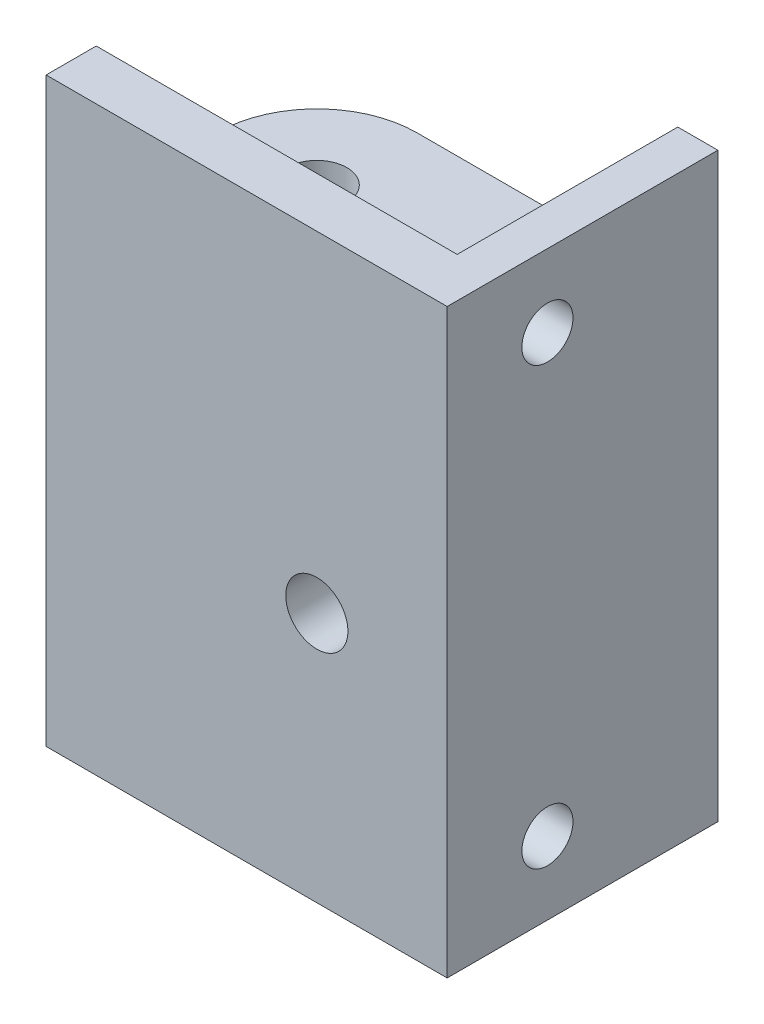
SolidWorks part; units mm, degrees
ref_plane "前视基准面" through (0, 0, 0) normal (0, 0, 1) x (1, 0, 0)
ref_plane "上视基准面" through (0, 0, 0) normal (0, 1, 0) x (1, 0, 0)
ref_plane "右视基准面" through (0, 0, 0) normal (1, 0, 0) x (0, 0, -1)
other "Configuration Table"
sketch "草图1" plane through (0, 0, 0) normal (0, 1, 0) x (1, 0, 0)
  line L0 (-20, 13.5) -> (5, 13.5)
  line L1 (20, -1.5) -> (20, -13.5)
  line L6 (-20, -13.5) -> (20, -13.5)
  line L7 (-20, -13.5) -> (-20, 13.5)
  arc A0 (20, -1.5) -> (5, 13.5) centre (5, -1.5) ccw
extrude "凸台-拉伸1" add sketch "草图1" along normal blind 58 contours L1 L6 L7 L0 A0
sketch "草图2" plane through (0, 0, 13.5) normal (0, 0, 1) x (1, 0, 0)
  circle A0 centre (-7, 33) radius 3
extrude "切除-拉伸1" cut sketch "草图2" against normal blind 58 contours A0
sketch "草图3" plane through (0, 0, -13.5) normal (0, 0, -1) x (-1, 0, 0)
  line L0 (20, 58) -> (20, 0)
  line L1 (20, 29) -> (-5, 29)
  line L2 (-5, 58) -> (-5, 0) construction
  line L3 (-5, 29) -> (-5, 43.5)
  line L4 (-5, 29) -> (-5, 14.5)
  line L5 (-5, 43.5) -> (20, 43.5)
  line L6 (-5, 14.5) -> (20, 14.5)
  line L7 (20, 43.5) -> (-20, 43.5)
  line L8 (20, 43.5) -> (20, 58)
  line L9 (20, 58) -> (-20, 58)
  line L10 (-20, 43.5) -> (-20, 58)
  line L12 (20, 14.5) -> (-20, 14.5)
  line L13 (20, 14.5) -> (20, 0)
  line L14 (20, 0) -> (-20, 0)
  line L15 (-20, 14.5) -> (-20, 0)
  line M8 (-5, 0) -> (20, 0)
  line M9 (20, 0) -> (20, 58)
  line M10 (20, 58) -> (-5, 58)
  line M11 (-5, 58) -> (-5, 0)
extrude "切除-拉伸2" cut sketch "草图3" against normal blind 22 contours L10 L7 L9 M11 | L12 L15 L14 M11 | L6 M11 M8 M9 | L5 M11 M9 M10
sketch "草图5" plane through (0, 0, 8.5) normal (0, 0, -1) x (-1, 0, 0)
  line L0 (20, 43.5) -> (-5, 43.5) construction
  line L1 (20, 58) -> (16, 58)
  line L2 (20, 58) -> (20, 43.5)
  line L3 (20, 43.5) -> (16, 43.5)
  line L4 (16, 58) -> (16, 43.5)
  line L5 (20, 14.5) -> (-5, 14.5) construction
  line L6 (20, 0) -> (16, 0)
  line L7 (20, 0) -> (20, 14.5)
  line L8 (20, 14.5) -> (16, 14.5)
  line L9 (16, 0) -> (16, 14.5)
extrude "凸台-拉伸2" add sketch "草图5" along normal blind 22 contours L9 L6 L7 L8 | L2 L1 L4 L3
sketch "草图8" plane through (-20, 0, 0) normal (-1, 0, 0) x (0, 0, 1)
  line L0 (13.5, 58) -> (3.5, 58)
  line L2 (-13.5, 58) -> (8.5, 58) construction
  line L3 (3.5, 58) -> (3.5, 43.5)
  line L4 (8.5, 43.5) -> (1.5, 43.5) construction
  line L5 (13.5, 0) -> (3.5, 0)
  line L6 (-13.5, 0) -> (8.5, 0) construction
  line L7 (3.5, 0) -> (3.5, 14.5)
  line L8 (8.5, 14.5) -> (1.5, 14.5) construction
  circle A0 centre (3.5, 50.75) radius 2.55
  circle A1 centre (3.5, 7.25) radius 2.55
extrude "切除-拉伸3" cut sketch "草图8" against normal blind 22 contours L3 A0 | L3 A0 | L7 A1 | L7 A1
sketch "草图10" plane through (0, 43.5, 0) normal (0, 1, 0) x (1, 0, 0)
  line L0 (20, -13.5) -> (20, -6.5)
  line L1 (20, -8.5) -> (20, -1.5) construction
  line L6 (20, 13.5) -> (20, -6.5)
  line L8 (-16, 13.5) -> (5, 13.5) construction
  line L9 (0, 13.5) -> (20, 13.5)
  arc A0 (20, -6.5) -> (0, 13.5) centre (20, 13.5) cw
  line M9 (5, 13.5) -> (-16, 13.5)
  line M12 (20, -8.5) -> (20, -1.5)
  arc M13 (20, -1.5) -> (5, 13.5) centre (5, -1.5) ccw
extrude "切除-拉伸4" cut sketch "草图10" against normal blind 30 contours A0 M12 M13 M9 | L9 L6 M13
sketch "草图11" plane through (0, 43.5, 0) normal (0, 1, 0) x (1, 0, 0)
  line L0 (0, 13.5) -> (5, 13.5)
  line L2 (20, -1.5) -> (20, -6.5)
  arc A0 (5, 13.5) -> (20, -1.5) centre (5, -1.5) cw
  arc A1 (0, 13.5) -> (20, -6.5) centre (20, 13.5) ccw
  arc A2 (0, 13.5) -> (20, -6.5) centre (20, 13.5) ccw construction
  circle A3 centre (9.5, 4) radius 1.51
  arc M15 (20, -6.5) -> (0, 13.5) centre (20, 13.5) cw
extrude "凸台-拉伸5" add sketch "草图11" against normal blind 4 contours A0 L0 L2 A3 M15
sketch "草图13" plane through (0, 14.5, 0) normal (0, -1, 0) x (1, 0, 0)
  line L0 (0, -13.5) -> (5, -13.5)
  line L2 (20, 6.5) -> (20, 1.5)
  arc A0 (0, -13.5) -> (20, 6.5) centre (20, -13.5) cw
  arc A1 (20, 1.5) -> (5, -13.5) centre (5, 1.5) cw
extrude "凸台-拉伸6" add sketch "草图13" against normal blind 4 contours A1 L2 A0 L0
sketch "草图17" plane through (0, 43.5, 0) normal (0, 1, 0) x (1, 0, 0)
  line L0 (20, -1.5) -> (20, 13.5)
  line L1 (20, -1.5) -> (20, -6.5)
  line L2 (20, -8.5) -> (20, -1.5) construction
  line L3 (-16, 13.5) -> (5, 13.5) construction
  line L4 (0, 13.5) -> (20, 13.5)
  line L6 (5.8579, -0.6421) -> (12.9289, 6.4289)
  arc A0 (20, -6.5) -> (0, 13.5) centre (20, 13.5) cw
  circle A1 centre (12.9289, 6.4289) radius 1.51
sketch "草图18" plane through (0, 0, 13.5) normal (0, 0, 1) x (1, 0, 0)
  circle A0 centre (-7, 33) radius 3.05
extrude "切除-拉伸7" cut sketch "草图18" against normal blind 50
extrude "切除-拉伸8" cut sketch "草图17" against normal blind 50
sketch "草图19" plane through (0, 43.5, 0) normal (0, 1, 0) x (1, 0, 0)
  line L2 (10, 13.5) -> (5, 13.5)
  line L3 (20, 3.5) -> (20, -1.5)
  arc A0 (5, 13.5) -> (20, -1.5) centre (5, -1.5) cw
  arc A1 (10, 13.5) -> (20, 3.5) centre (10, 3.5) cw
extrude "凸台-拉伸7" add sketch "草图19" against normal blind 4 contours L3 A0 L2 A1
sketch "草图20" plane through (0, 43.5, 0) normal (0, 1, 0) x (1, 0, 0)
  line L2 (20, 3.5) -> (20, -8.5)
  line L3 (20, -8.5) -> (-16, -8.5)
  line L4 (-16, -8.5) -> (-16, 13.5)
  line L5 (-16, 13.5) -> (10, 13.5)
  arc A0 (10, 13.5) -> (20, 3.5) centre (10, 3.5) cw
  arc A1 (20, 3.5) -> (10, 13.5) centre (10, 3.5) ccw construction
  circle A2 centre (12.9289, 6.4289) radius 1.51
extrude "凸台-拉伸8" add sketch "草图20" along normal blind 1 contours A0 L2 L3 L4 L5
sketch "草图21" plane through (0, 44.5, 0) normal (0, 1, 0) x (1, 0, 0)
  circle A0 centre (12.9289, 6.4289) radius 3
  circle M2 centre (12.9289, 6.4289) radius 1.51
extrude "切除-拉伸9" cut sketch "草图21" against normal blind 2 contours A0 M2
sketch "草图22" plane through (0, 14.5, 0) normal (0, -1, 0) x (-1, 0, 0)
  line L0 (-5, 13.5) -> (-10, 13.5)
  line L1 (-20, -1.5) -> (-20, 3.5)
  arc A0 (-10, 13.5) -> (-20, 3.5) centre (-10, 3.5) ccw
  arc A1 (-5, 13.5) -> (-20, -1.5) centre (-5, -1.5) ccw
  arc A2 (-5, 13.5) -> (-20, -1.5) centre (-5, -1.5) ccw construction
extrude "凸台-拉伸9" add sketch "草图22" against normal blind 4 contours L0 A0 L1 A1
sketch "草图23" plane through (0, 14.5, 0) normal (0, -1, 0) x (-1, 0, 0)
  line L0 (16, -8.5) -> (16, 13.5)
  line L1 (16, 13.5) -> (-10, 13.5)
  line L4 (-20, 3.5) -> (-20, -8.5)
  line L5 (-20, -8.5) -> (16, -8.5)
  arc A0 (-10, 13.5) -> (-20, 3.5) centre (-10, 3.5) ccw
  arc A1 (-10, 13.5) -> (-20, 3.5) centre (-10, 3.5) ccw construction
  circle A2 centre (-12.9289, 6.4289) radius 1.51
extrude "凸台-拉伸10" add sketch "草图23" along normal blind 1 contours A0 L4 L5 L0 L1
sketch "草图24" plane through (0, 13.5, 0) normal (0, -1, 0) x (-1, 0, 0)
  circle A0 centre (-12.9289, 6.4289) radius 3
extrude "切除-拉伸10" cut sketch "草图24" against normal blind 2
sketch "草图25" plane through (0, 0, 13.5) normal (0, 0, 1) x (1, 0, 0)
  line L0 (-7, 29) -> (-20, 29)
  line L1 (-20, 58) -> (20, 58) construction
  line L2 (-7, 58) -> (-7, 0)
  line L3 (-20, 0) -> (20, 0) construction
  line L4 (-20, 58) -> (-20, 0) construction
  circle A1 centre (-7, 33) radius 3.05
  circle A2 centre (-7, 25) radius 3.05
extrude "切除-拉伸11" cut sketch "草图25" against normal blind 100 contours A2 L2 | A2 L2
sketch "草图26" plane through (0, 0, 13.5) normal (0, 0, 1) x (1, 0, 0)
  circle A0 centre (-7, 33) radius 3.05
extrude "凸台-拉伸11" add sketch "草图26" against normal blind 27 contours A0
sketch "草图27" plane through (0, 0, 13.5) normal (0, 0, 1) x (1, 0, 0)
  circle A0 centre (-7, 25) radius 3.1
extrude "切除-拉伸12" cut sketch "草图27" against normal blind 27
sketch "草图29" plane through (0, 0, -13.5) normal (0, 0, -1) x (-1, 0, 0)
  line L1 (0, 39.5) -> (-20, 39.5)
  line L2 (0, 39.5) -> (0, 18.5)
  line L3 (0, 18.5) -> (-20, 18.5)
  line L4 (-20, 39.5) -> (-20, 18.5)
extrude "切除-拉伸13" cut sketch "草图29" against normal blind 20 contours L2 L1 L4 L3
sketch "草图30" plane through (0, 13.5, 0) normal (0, -1, 0) x (-1, 0, 0)
  circle A0 centre (-12.9289, 6.4289) radius 3
extrude "凸台-拉伸12" add sketch "草图30" against normal blind 5 contours A0
sketch "草图32" plane through (0, 44.5, 0) normal (0, 1, 0) x (1, 0, 0)
  circle A0 centre (12.9289, 6.4289) radius 3
extrude "凸台-拉伸13" add sketch "草图32" against normal blind 5 contours A0
sketch "草图34" plane through (0, 44.5, 0) normal (0, 1, 0) x (1, 0, 0)
  line L3 (-16, -8.5) -> (10.5, -8.5)
  line L4 (-16, -8.5) -> (20, -8.5) construction
  line L5 (10.5, -8.5) -> (10.5, 4)
  circle A0 centre (10.5, 4) radius 1.51
extrude "切除-拉伸14" cut sketch "草图34" against normal blind 100
sketch "草图35" plane through (0, 44.5, 0) normal (0, 1, 0) x (1, 0, 0)
  circle A0 centre (10.5, 4) radius 3
extrude "切除-拉伸15" cut sketch "草图35" against normal blind 2
sketch "草图36" plane through (0, 13.5, 0) normal (0, -1, 0) x (-1, 0, 0)
  circle A0 centre (-10.5, 4) radius 3
extrude "切除-拉伸16" cut sketch "草图36" against normal blind 2
mirror "镜向1" about plane through (-20, 58, 13.5) normal (-1, 0, 0) of "切除-拉伸3", "切除-拉伸14", "凸台-拉伸1", "切除-拉伸2", "凸台-拉伸2", "凸台-拉伸5", "凸台-拉伸6", "凸台-拉伸7", "凸台-拉伸8", "凸台-拉伸9", "凸台-拉伸10", "切除-拉伸12", "切除-拉伸13", "切除-拉伸15", "切除-拉伸16"
sketch "草图38" plane through (0, 0, -13.5) normal (0, 0, -1) x (-1, 0, 0)
  line L0 (24, 58) -> (16, 58) construction
  line L1 (-20, 0) -> (20, 0)
  line L2 (-20, 0) -> (-20, 58)
  line L3 (-20, 58) -> (20, 58)
  line L4 (20, 0) -> (20, 58)
extrude "切除-拉伸17" cut sketch "草图38" against normal blind 50 contours L2 L1 L4 L3
sketch "草图40" plane through (0, 13.5, 0) normal (0, -1, 0) x (-1, 0, 0)
  circle A0 centre (52.9289, 6.4289) radius 1.51
extrude "凸台-拉伸14" add sketch "草图40" against normal blind 1
sketch "草图41" plane through (0, 13.5, 0) normal (0, -1, 0) x (-1, 0, 0)
  circle A0 centre (50.5, 4) radius 3
extrude "切除-拉伸18" cut sketch "草图41" against normal blind 1 contours A0
sketch "草图42" plane through (0, 44.5, 0) normal (0, 1, 0) x (1, 0, 0)
  circle A0 centre (-52.9289, 6.4289) radius 1.51
extrude "凸台-拉伸15" add sketch "草图42" against normal blind 1 contours A0
sketch "草图43" plane through (0, 44.5, 0) normal (0, 1, 0) x (1, 0, 0)
  circle A0 centre (-50.5, 4) radius 3
extrude "切除-拉伸19" cut sketch "草图43" against normal blind 1 contours A0
